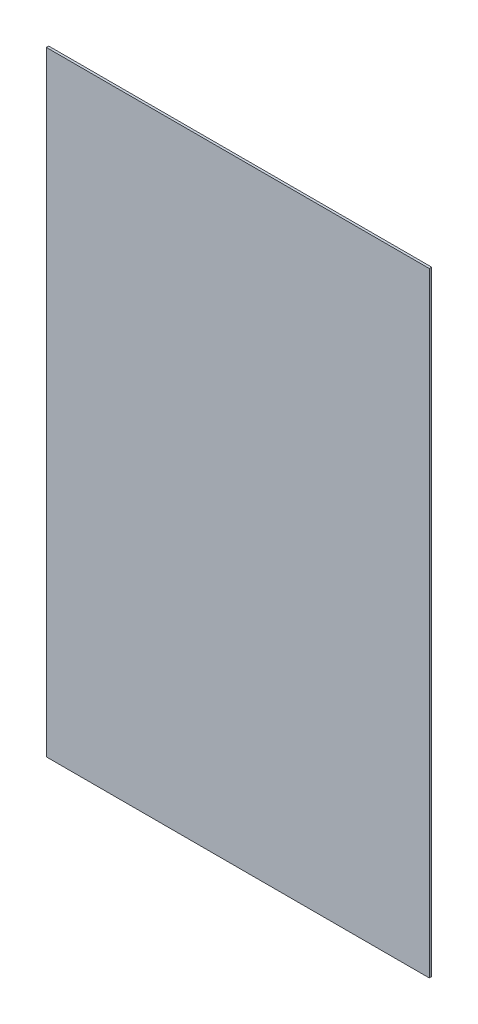
SolidWorks part; units mm, degrees
ref_plane "Front Plane" through (0, 0, 0) normal (0, 0, 1) x (1, 0, 0)
ref_plane "Top Plane" through (0, 0, 0) normal (0, 1, 0) x (1, 0, 0)
ref_plane "Right Plane" through (0, 0, 0) normal (1, 0, 0) x (0, 0, -1)
sketch "Sketch1" plane through (0, 0, 0) normal (0, 0, 1) x (1, 0, 0)
  line L1 (-413.3684, 286.386) -> (66.6316, 286.386)
  line L2 (-413.3684, 286.386) -> (-413.3684, -483.614)
  line L3 (-413.3684, -483.614) -> (66.6316, -483.614)
  line L4 (66.6316, 286.386) -> (66.6316, -483.614)
  dimension "D1" = 480
  dimension "D2" = 770
extrude "Boss-Extrude1" add sketch "Sketch1" along normal blind 3
